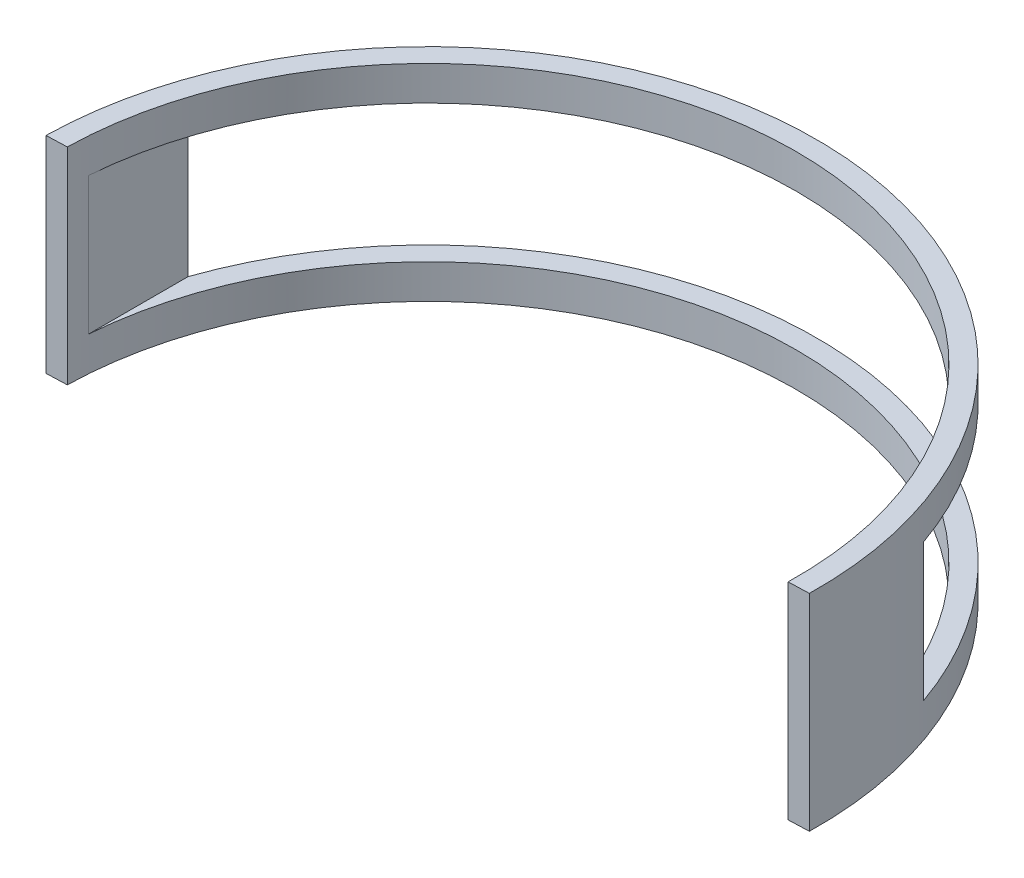
SolidWorks part; units mm, degrees
ref_plane "Front Plane" through (0, 0, 0) normal (0, 0, 1) x (1, 0, 0)
ref_plane "Top Plane" through (0, 0, 0) normal (0, 1, 0) x (1, 0, 0)
ref_plane "Right Plane" through (0, 0, 0) normal (1, 0, 0) x (0, 0, -1)
sketch "Sketch1" plane through (0, 0, 0) normal (0, 1, 0) x (1, 0, 0)
  line L0 (-56.6451, 1.0852) -> (-53.6469, 1.1868)
  line L1 (53.6469, -1.1868) -> (56.6451, -1.0849)
  arc A0 (56.6451, -1.0849) -> (-56.6451, 1.0852) centre (0, 0) ccw
  arc A1 (53.6469, -1.1868) -> (-53.6469, 1.1868) centre (0, 0) ccw
extrude "Boss-Extrude1" add sketch "Sketch1" along normal mid plane 30
sketch "Sketch3" plane through (0, 0, 0) normal (0, 0, 1) x (1, 0, 0)
  line L1 (-53.5, -10) -> (53.5, -10)
  line L2 (-53.5, -10) -> (-53.5, 10)
  line L3 (-53.5, 10) -> (53.5, 10)
  line L4 (53.5, -10) -> (53.5, 10)
  line L5 (-53.5, -10) -> (53.5, 10) construction
  line L6 (-53.5, 10) -> (53.5, -10) construction
  point P0 (0, 0)
extrude "Cut-Extrude1" cut sketch "Sketch3" against normal blind 200 and the other way through all
